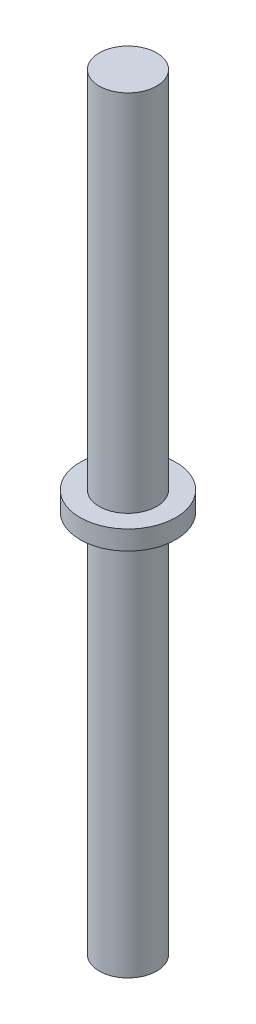
SolidWorks part; units mm, degrees
ref_plane "Front Plane" through (0, 0, 0) normal (0, 0, 1) x (1, 0, 0)
ref_plane "Top Plane" through (0, 0, 0) normal (0, 1, 0) x (1, 0, 0)
ref_plane "Right Plane" through (0, 0, 0) normal (1, 0, 0) x (0, 0, -1)
sketch "Sketch1" plane through (0, 0, 0) normal (0, 1, 0) x (1, 0, 0)
  circle A0 centre (0, 0) radius 7.5
  dimension "D1" = 15
extrude "Boss-Extrude1" add sketch "Sketch1" along normal blind 200
sketch "Sketch2" plane through (0, 200, 0) normal (0, 1, 0) x (1, 0, 0)
  circle A0 centre (0, 0) radius 12.5
  dimension "D1" = 25
extrude "Boss-Extrude2" add sketch "Sketch2" along normal blind 5 from offset 100 offset against normal yes
